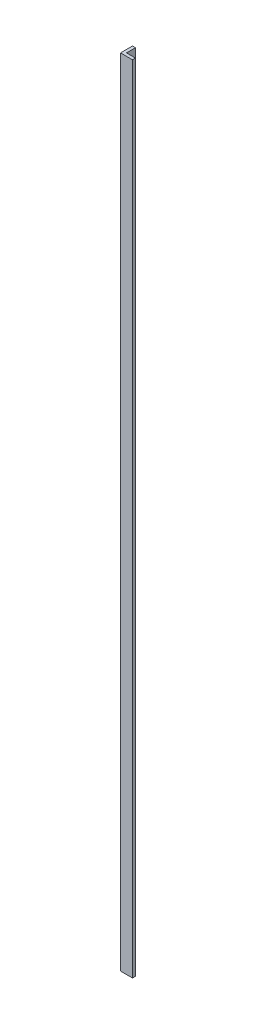
SolidWorks part; units mm, degrees
ref_plane "Front Plane" through (0, 0, 0) normal (0, 0, 1) x (1, 0, 0)
ref_plane "Top Plane" through (0, 0, 0) normal (0, 1, 0) x (1, 0, 0)
ref_plane "Right Plane" through (0, 0, 0) normal (1, 0, 0) x (0, 0, -1)
sketch "Sketch1" plane through (0, 0, 0) normal (0, 1, 0) x (1, 0, 0)
  line L1 (0, 0) -> (6.35, 0)
  line L2 (0, 0) -> (0, 6.35)
  line L3 (0, 6.35) -> (1.5875, 6.35)
  line L4 (6.35, 0) -> (6.35, 1.5875)
  line L7 (6.35, 1.5875) -> (1.5875, 1.5875)
  line L8 (1.5875, 6.35) -> (1.5875, 1.5875)
  dimension "D1" = 6.35
  dimension "D2" = 6.35
  dimension "D3" = 1.5875
  dimension "D4" = 1.5875
extrude "Boss-Extrude1" add sketch "Sketch1" along normal blind 423.545
